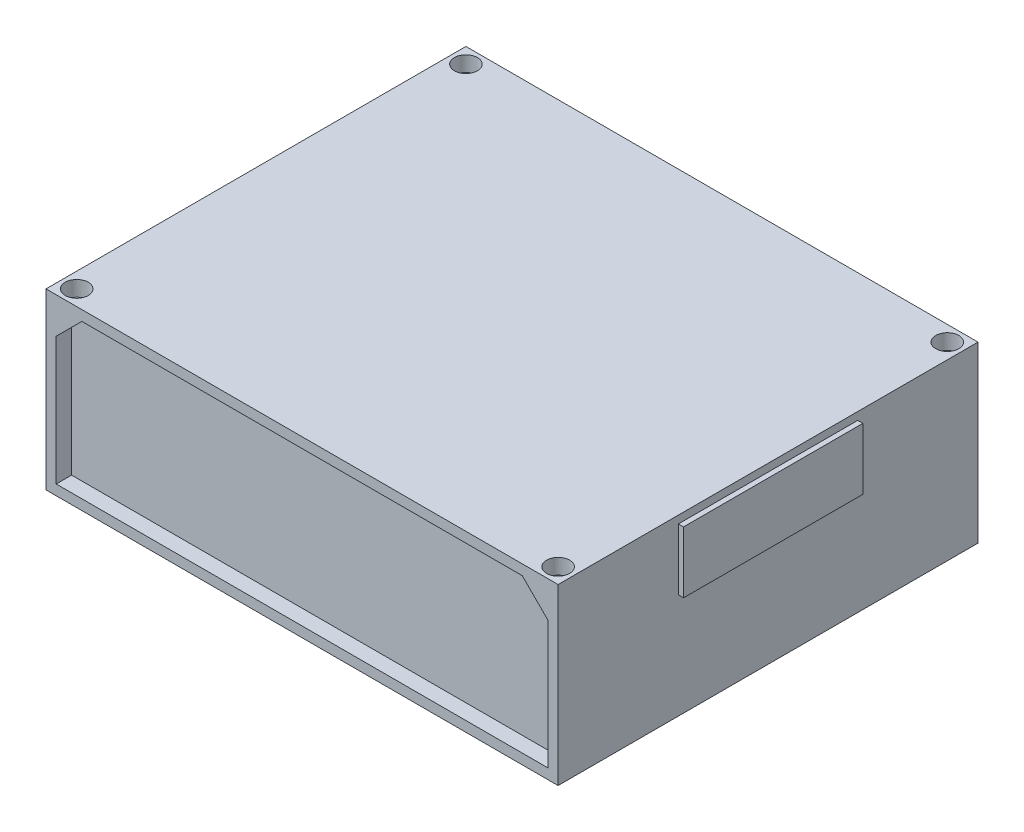
SolidWorks part; units mm, degrees
ref_plane "Front Plane" through (0, 0, 0) normal (0, 0, 1) x (1, 0, 0)
ref_plane "Top Plane" through (0, 0, 0) normal (0, 1, 0) x (1, 0, 0)
ref_plane "Right Plane" through (0, 0, 0) normal (1, 0, 0) x (0, 0, -1)
sketch "Sketch1" plane through (0, 0, 0) normal (0, 1, 0) x (1, 0, 0)
  line L1 (0, 0) -> (100, 0)
  line L2 (0, 0) -> (0, 82)
  line L3 (0, 82) -> (100, 82)
  line L4 (100, 0) -> (100, 82)
  dimension "D1" = 82
  dimension "D2" = 100
extrude "Boss-Extrude1" add sketch "Sketch1" along normal blind 34
ref_plane "Plane1" through (0, 0, -41) normal (0, 0, 1) x (1, 0, 0)
sketch "Sketch2" plane through (0, 0, 0) normal (0, 0, 1) x (1, 0, 0)
  line L0 (0, 17) -> (100, 17) construction
  line L1 (0, 34) -> (0, 0) construction
  line L2 (100, 34) -> (100, 0) construction
  line L3 (0, 34) -> (100, 34) construction
  line L4 (98, 2) -> (2, 2)
  line L5 (98, 2) -> (98, 32)
  line L6 (98, 32) -> (2, 32)
  line L7 (2, 2) -> (2, 32)
  line L8 (98, 2) -> (2, 32) construction
  line L9 (98, 32) -> (2, 2) construction
  point P6 (50, 17)
  dimension "D1" = 2
  dimension "D2" = 2
extrude "Cut-Extrude1" cut sketch "Sketch2" against normal blind 3
chamfer "Chamfer1" distance 5 angle 45 2 edges at (98, 32, -1.5) (2, 32, -1.5)
mirror "Mirror4" about plane through (0, 0, -41) normal (0, 0, 1) of "Cut-Extrude1", "Chamfer1"
sketch "Sketch3" plane through (0, 34, 0) normal (0, 1, 0) x (1, 0, 0)
  line L0 (0, 41) -> (100, 41) construction
  line L1 (0, 82) -> (0, 0) construction
  line L2 (100, 0) -> (100, 82) construction
  line L3 (100, 82) -> (0, 82) construction
  line L4 (97, 3) -> (3, 3) construction
  line L5 (97, 3) -> (97, 79) construction
  line L6 (97, 79) -> (3, 79) construction
  line L7 (3, 3) -> (3, 79) construction
  line L8 (97, 3) -> (3, 79) construction
  line L9 (97, 79) -> (3, 3) construction
  circle A0 centre (3, 79) radius 2.25
  circle A1 centre (3, 3) radius 2.25
  circle A2 centre (97, 3) radius 2.25
  circle A3 centre (97, 79) radius 2.25
  point P6 (50, 41)
  dimension "D3" = 4.5
  dimension "D4" = 4.5
  dimension "D5" = 4.5
  dimension "D6" = 4.5
  dimension "D1" = 3
  dimension "D2" = 3
extrude "Cut-Extrude2" cut sketch "Sketch3" against normal blind 3
sketch "Sketch4" plane through (100, 0, 0) normal (1, 0, 0) x (0, 0, -1)
  line L0 (0, 17) -> (82, 17) construction
  line L1 (0, 34) -> (0, 0) construction
  line L2 (82, 34) -> (82, 0) construction
  line L3 (41, 34) -> (41, 0) construction
  line L4 (0, 34) -> (82, 34) construction
  line L5 (0, 0) -> (82, 0) construction
  line L7 (58.5, 20.5) -> (23.5, 20.5)
  line L8 (58.5, 20.5) -> (58.5, 32.5)
  line L9 (58.5, 32.5) -> (23.5, 32.5)
  line L10 (23.5, 20.5) -> (23.5, 32.5)
  line L11 (58.5, 20.5) -> (23.5, 32.5) construction
  line L12 (58.5, 32.5) -> (23.5, 20.5) construction
  point P12 (41, 26.5)
  dimension "D1" = 12
  dimension "D2" = 35
  dimension "D3" = 3.5
extrude "Boss-Extrude2" add sketch "Sketch4" along normal blind 1
